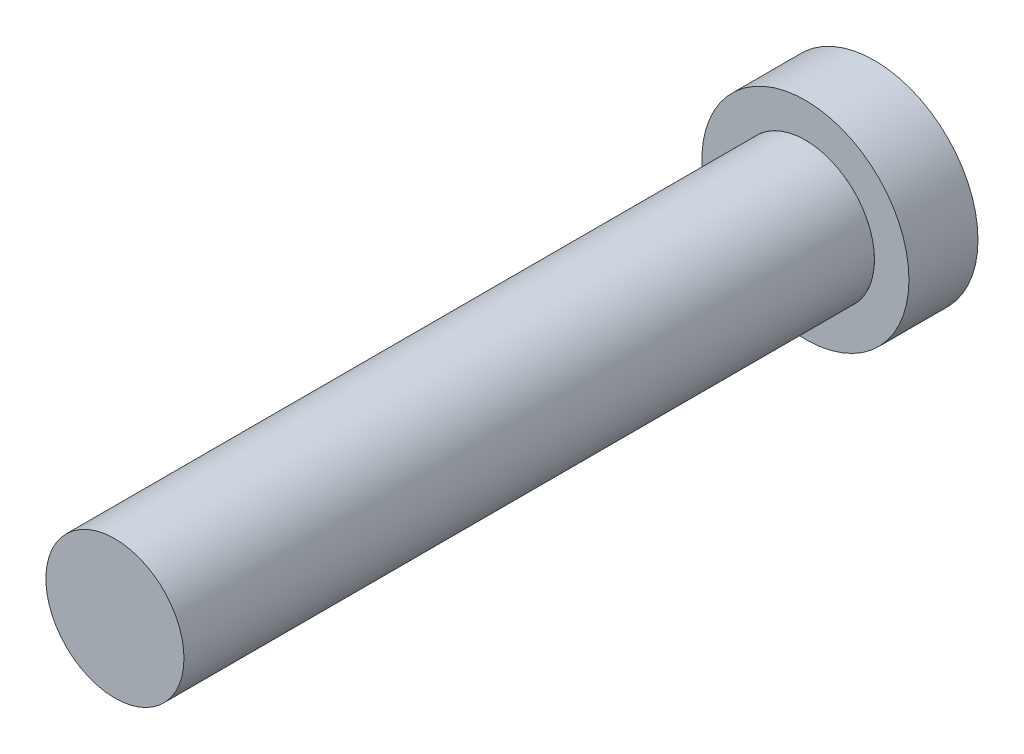
SolidWorks part; units mm, degrees
ref_plane "Front Plane" through (0, 0, 0) normal (0, 0, 1) x (1, 0, 0)
ref_plane "Top Plane" through (0, 0, 0) normal (0, 1, 0) x (1, 0, 0)
ref_plane "Right Plane" through (0, 0, 0) normal (1, 0, 0) x (0, 0, -1)
sketch "Sketch2" plane through (0, 0, 0) normal (1, 0, 0) x (0, 0, -1)
  line L0 (0, 0) -> (550, 0)
  line L1 (550, 0) -> (550, -75)
  line L2 (550, -75) -> (500, -75)
  line L3 (500, -75) -> (500, -50)
  line L4 (500, -50) -> (0, -50)
  line L5 (0, -50) -> (0, 0)
  dimension "D1" = 550
  dimension "D2" = 50
  dimension "D3" = 50
  dimension "D4" = 25
revolve "Revolve1" add sketch "Sketch2" angle 360 about L0
sketch "Sketch4" plane through (0, 0, -550) normal (0, 0, -1) x (-1, 0, 0)
  circle A0 centre (0, 0) radius 50
  dimension "D1" = 100
extrude "Cut-Extrude2" cut sketch "Sketch4" against normal blind 50
